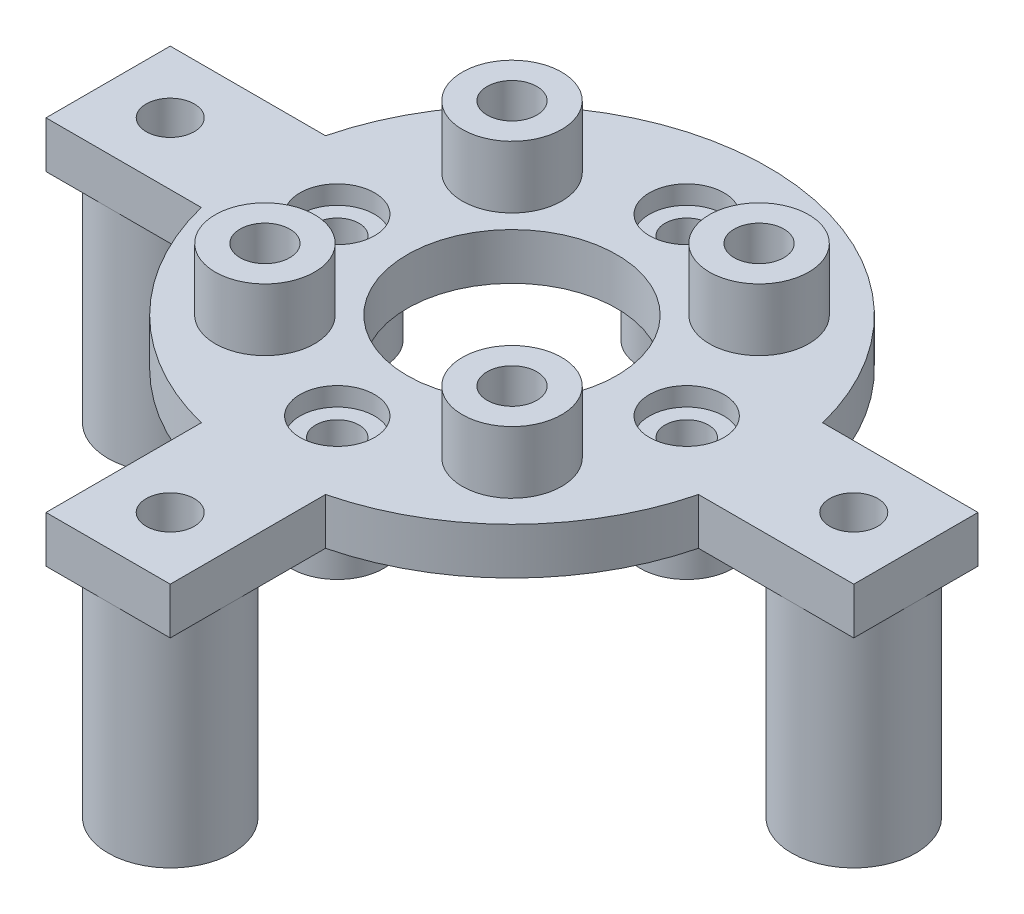
SolidWorks part; units mm, degrees
ref_plane "前视基准面" through (0, 0, 0) normal (0, 0, 1) x (1, 0, 0)
ref_plane "上视基准面" through (0, 0, 0) normal (0, 1, 0) x (1, 0, 0)
ref_plane "右视基准面" through (0, 0, 0) normal (1, 0, 0) x (0, 0, -1)
sketch "草图1" plane through (0, 0, 0) normal (0, 1, 0) x (1, 0, 0)
  circle A0 centre (0, 0) radius 16.5
  circle A1 centre (0, 11.25) radius 1.4
  circle A2 centre (11.25, 0) radius 1.4
  circle A3 centre (0, -11.25) radius 1.4
  circle A4 centre (-11.25, 0) radius 1.4
  circle A5 centre (0, 0) radius 6.75
  point P14 (0, 0)
  dimension "D1" = 33
  dimension "D2" = 2.8
  dimension "D4" = 13.5
  dimension "D5" = 11.25
  dimension "D3" = 4
extrude "凸台-拉伸1" add sketch "草图1" along normal blind 3
sketch "草图2" plane through (0, 3, 0) normal (0, 1, 0) x (1, 0, 0)
  circle A1 centre (7.955, 7.955) radius 3.2
  circle A3 centre (7.955, -7.955) radius 3.2
  circle A5 centre (-7.955, -7.955) radius 3.2
  circle A7 centre (-7.955, 7.955) radius 3.2
  point P20 (0, 0)
  dimension "D2" = 6.4
extrude "凸台-拉伸2" add sketch "草图2" along normal blind 4
sketch "草图3" plane through (0, 7, 0) normal (0, 1, 0) x (1, 0, 0)
  circle A0 centre (-7.955, 7.955) radius 1.6
  circle A1 centre (7.955, 7.955) radius 1.6
  circle A2 centre (-7.955, -7.955) radius 1.6
  circle A3 centre (7.955, -7.955) radius 1.6
  dimension "D1" = 3.2
extrude "切除-拉伸3" cut sketch "草图3" against normal through all
sketch "草图4" plane through (0, 0, 0) normal (0, -1, 0) x (1, 0, 0)
  circle A0 centre (0, 11.25) radius 1.4 construction
  circle A1 centre (-11.25, 0) radius 1.4 construction
  circle A2 centre (11.25, 0) radius 1.4 construction
  circle A3 centre (0, -11.25) radius 1.4 construction
  circle A4 centre (0, 11.25) radius 1.4
  circle A5 centre (-11.25, 0) radius 1.4
  circle A6 centre (11.25, 0) radius 1.4
  circle A7 centre (0, -11.25) radius 1.4
  circle A8 centre (0, -11.25) radius 3
  circle A9 centre (-11.25, 0) radius 3
  circle A10 centre (0, 11.25) radius 3
  circle A11 centre (11.25, 0) radius 3
  point P22 (0, 0)
  dimension "D1" = 6
  dimension "D2" = 4
extrude "凸台-拉伸3" add sketch "草图4" along normal blind 4
sketch "草图5" plane through (0, 3, 0) normal (0, 1, 0) x (1, 0, 0)
  circle A0 centre (0, 11.25) radius 2.4
  circle A1 centre (11.25, 0) radius 2.4
  circle A2 centre (0, -11.25) radius 2.4
  circle A3 centre (-11.25, 0) radius 2.4
  point P12 (0, 0)
  dimension "D1" = 4.8
  dimension "D2" = 4
extrude "切除-拉伸4" cut sketch "草图5" against normal blind 1.2
sketch "草图6" plane through (0, 0, 0) normal (0, -1, 0) x (1, 0, 0)
  line L0 (0, 0) -> (-16.0078, 0) construction
  line L1 (-26.0078, 4) -> (-16.0078, 4)
  line L2 (-26.0078, 4) -> (-26.0078, -4)
  line L3 (-26.0078, -4) -> (-16.0078, -4)
  line L4 (-16.0078, 4) -> (-16.0078, -4)
  line L5 (-26.0078, 4) -> (-16.0078, -4) construction
  line L6 (-26.0078, -4) -> (-16.0078, 4) construction
  line L7 (4, 26.0078) -> (-4, 26.0078)
  line L12 (4, 26.0078) -> (4, 16.0078)
  line L13 (4, 16.0078) -> (-4, 16.0078)
  line L14 (-4, 26.0078) -> (-4, 16.0078)
  line L15 (26.0078, -4) -> (26.0078, 4)
  line L16 (26.0078, -4) -> (16.0078, -4)
  line L17 (16.0078, -4) -> (16.0078, 4)
  line L18 (26.0078, 4) -> (16.0078, 4)
  line L19 (0, 0) -> (-16.0078, 4) construction
  line L20 (0, 0) -> (4, 16.0078) construction
  circle A0 centre (0, 0) radius 16.5 construction
  point P0 (-21.0078, 0)
  dimension "D1" = 10
  dimension "D2" = 8
  dimension "D4" = 90
  dimension "D3" = 3
extrude "凸台-拉伸4" add sketch "草图6" against normal up to surface (3 mm away) up to face at (0, 3, -8.85)
sketch "草图7" plane through (0, 0, 0) normal (0, 1, 0) x (1, 0, 0)
  line L0 (-26.0078, -4) -> (-26.0078, 4) construction
  line L1 (-26.0078, 4) -> (-16.0078, 4) construction
  line L2 (0, 0) -> (-22.0078, 0) construction
  line L3 (0, 0) -> (0, -22.0078) construction
  circle A0 centre (-22.0078, 0) radius 4
  circle A5 centre (0, -22.0078) radius 4
  circle A6 centre (22.0078, 0) radius 4
  dimension "D1" = 8
  dimension "D3" = 90
  dimension "D2" = 3
extrude "凸台-拉伸5" add sketch "草图7" against normal blind 14
sketch "草图8" plane through (0, -14, 0) normal (0, -1, 0) x (1, 0, 0)
  line L0 (0, 0) -> (-22.0078, 0) construction
  line L1 (0, 0) -> (0, 22.0078) construction
  circle A0 centre (-22.0078, 0) radius 1.55
  circle A1 centre (0, 22.0078) radius 1.55
  circle A2 centre (22.0078, 0) radius 1.55
  dimension "D1" = 3.1
  dimension "D3" = 90
  dimension "D2" = 3
extrude "切除-拉伸5" cut sketch "草图8" against normal through all
